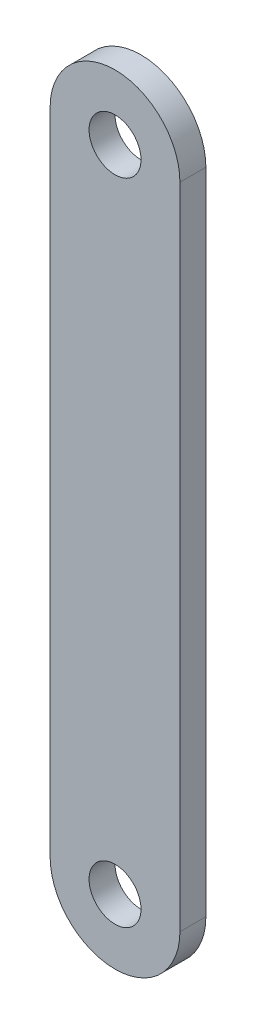
SolidWorks part; units mm, degrees
ref_plane "Alzado" through (0, 0, 0) normal (0, 0, 1) x (1, 0, 0)
ref_plane "Planta" through (0, 0, 0) normal (0, 1, 0) x (1, 0, 0)
ref_plane "Vista lateral" through (0, 0, 0) normal (1, 0, 0) x (0, 0, -1)
sketch "Croquis1" plane through (0, 0, 0) normal (0, 0, 1) x (1, 0, 0)
  line L0 (0, 0) -> (50, 0) construction
  line L1 (50, 0) -> (50, 250)
  line L2 (50, 250) -> (0, 250) construction
  line L3 (0, 250) -> (0, 0)
  arc A0 (0, 0) -> (50, 0) centre (25, 0) ccw
  arc A1 (50, 250) -> (0, 250) centre (25, 250) ccw
  circle A2 centre (25, 250) radius 10
  circle A3 centre (25, 0) radius 10
  dimension "D3" = 20
  dimension "D4" = 20
  dimension "D1" = 50
  dimension "D2" = 250
extrude "Saliente-Extruir1" add sketch "Croquis1" along normal blind 10
